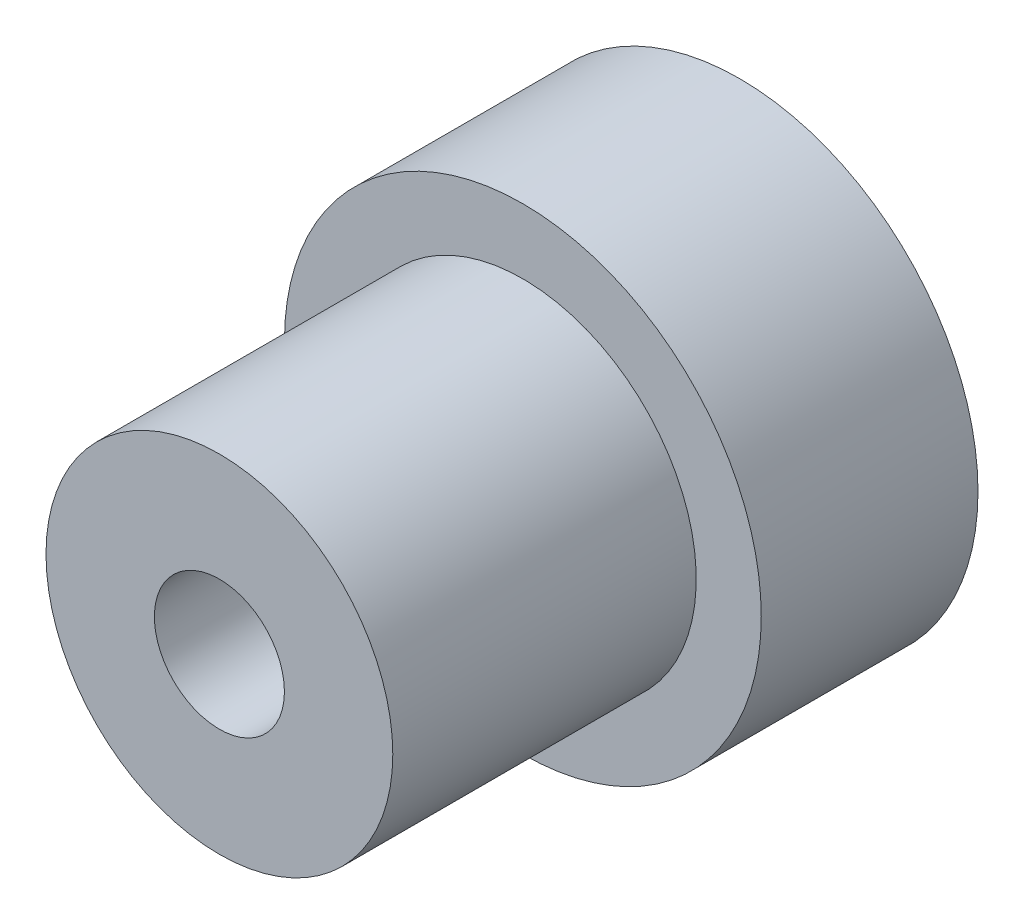
SolidWorks part; units mm, degrees
ref_plane "前视基准面" through (0, 0, 0) normal (0, 0, 1) x (1, 0, 0)
ref_plane "上视基准面" through (0, 0, 0) normal (0, 1, 0) x (1, 0, 0)
ref_plane "右视基准面" through (0, 0, 0) normal (1, 0, 0) x (0, 0, -1)
sketch "草图1" plane through (0, 0, 0) normal (0, 0, 1) x (1, 0, 0)
  circle A0 centre (0, 0) radius 4
  dimension "D1" = 8
extrude "拉伸1" add sketch "草图1" along normal blind 12
sketch "草图2" plane through (0, 0, 0) normal (0, 0, -1) x (-1, 0, 0)
  circle A0 centre (0, 0) radius 5.5
  dimension "D1" = 11
extrude "拉伸2" add sketch "草图2" against normal blind 5
sketch "草图3" plane through (0, 0, 0) normal (0, 0, -1) x (-1, 0, 0)
  circle A0 centre (0, 0) radius 4
  dimension "D1" = 8
extrude "拉伸5" cut sketch "草图3" against normal blind 2
sketch "草图5" plane through (0, 0, 12) normal (0, 0, 1) x (1, 0, 0)
  circle A0 centre (0, 0) radius 1.5
  dimension "D1" = 3
extrude "拉伸6" cut sketch "草图5" against normal through all
